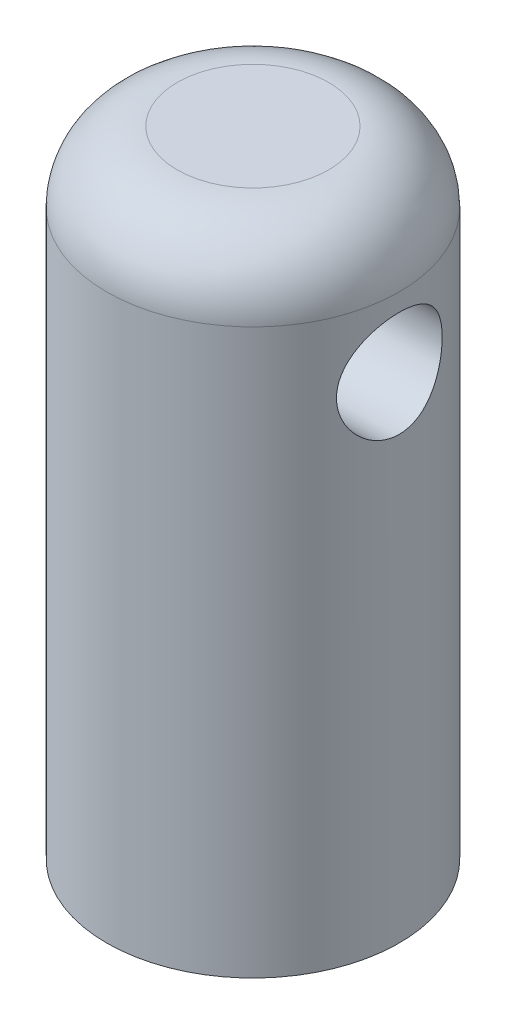
SolidWorks part; units mm, degrees
ref_plane "Front Plane" through (0, 0, 0) normal (0, 0, 1) x (1, 0, 0)
ref_plane "Top Plane" through (0, 0, 0) normal (0, 1, 0) x (1, 0, 0)
ref_plane "Right Plane" through (0, 0, 0) normal (1, 0, 0) x (0, 0, -1)
sketch "Sketch2" plane through (0, 0, 0) normal (0, 1, 0) x (1, 0, 0)
  circle A0 centre (0, 0) radius 1.75 construction
  circle A1 centre (0, 0) radius 4.15
  dimension "D1" = 3.5
  dimension "D2" = 2.4
extrude "Boss-Extrude1" add sketch "Sketch2" along normal blind 18
sketch "Sketch3" plane through (0, 0, 0) normal (0, -1, 0) x (1, 0, 0)
  circle A0 centre (0, 0) radius 1.75 construction
  circle A1 centre (0, 0) radius 1.75
extrude "Cut-Extrude1" cut sketch "Sketch3" against normal blind 10
sketch "Sketch4" plane through (0, 0, 0) normal (1, 0, 0) x (0, 0, -1)
  line L0 (0, 0) -> (0, 14) construction
  circle A0 centre (0, 14) radius 1.5
  dimension "D1" = 3
  dimension "D2" = 14
extrude "Cut-Extrude2" cut sketch "Sketch4" against normal through all both and the other way through all
fillet "Fillet1" radius 2 1 edges at (0, 18, 4.15)
